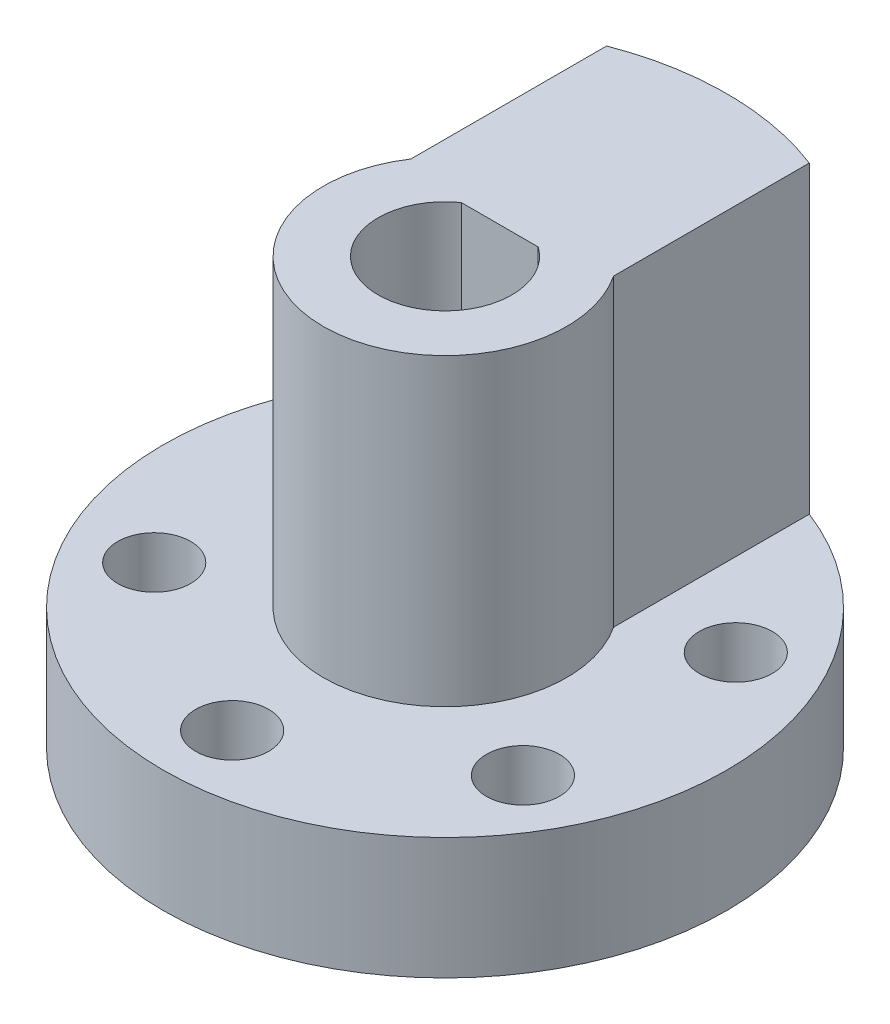
SolidWorks part; units mm, degrees
ref_plane "Plan de face" through (0, 0, 0) normal (0, 0, 1) x (1, 0, 0)
ref_plane "Plan de dessus" through (0, 0, 0) normal (0, 1, 0) x (1, 0, 0)
ref_plane "Plan de droite" through (0, 0, 0) normal (1, 0, 0) x (0, 0, -1)
sketch "Esquisse3" plane through (0, 0, 0) normal (0, 1, 0) x (1, 0, 0)
  circle A0 centre (0, 0) radius 13.9
  circle A2 centre (0, 0) radius 10.5 construction
  circle A3 centre (0, 10.5) radius 1.8
  circle A4 centre (9.0933, 5.25) radius 1.8
  circle A5 centre (9.0933, -5.25) radius 1.8
  circle A6 centre (0, -10.5) radius 1.8
  circle A7 centre (-9.0933, -5.25) radius 1.8
  circle A8 centre (-9.0933, 5.25) radius 1.8
  point P3 (0, 0)
  point P20 (0, 0)
  dimension "D1" = 27.8
  dimension "D2" = 6
  dimension "D3" = 21
  dimension "D4" = 3.6
extrude "Boss.-Extru.1" add sketch "Esquisse3" along normal blind 6
sketch "Esquisse5" plane through (0, 6, 0) normal (0, 1, 0) x (1, 0, 0)
  circle A0 centre (0, 0) radius 6
  dimension "D1" = 12
extrude "Boss.-Extru.2" add sketch "Esquisse5" along normal blind 15
sketch "Esquisse6" plane through (0, 21, 0) normal (0, 1, 0) x (1, 0, 0)
  line L0 (-1.8974, 2.7) -> (1.8974, 2.7)
  arc A0 (-1.8974, 2.7) -> (1.8974, 2.7) centre (0, 0) ccw
  point P1 (0, -3.3)
  dimension "D1" = 6
  dimension "D2" = 3.3
extrude "Enlèv. mat.-Extru.2" cut sketch "Esquisse6" against normal blind 11.8
ref_plane "Plan1" through (0, 0, 6) normal (0, 0, 1) x (1, 0, 0)
ref_plane "Plan2" through (0, 0, -6) normal (0, 0, -1) x (-1, 0, 0)
sketch "Esquisse7" plane through (0, 0, -6) normal (0, 0, -1) x (-1, 0, 0)
  line L0 (6, 21) -> (-6, 21) construction
  line L1 (-5, 21) -> (5, 21)
  line L2 (-5, 21) -> (-5, 6)
  line L3 (-5, 6) -> (5, 6)
  line L4 (5, 21) -> (5, 6)
  line L5 (-5, 21) -> (5, 6) construction
  line L6 (-5, 6) -> (5, 21) construction
  line L7 (6, 6) -> (-6, 6) construction
  point P3 (0, 21)
  point P9 (0, 0)
  dimension "D3" = 10
extrude "Boss.-Extru.3" add sketch "Esquisse7" along normal up to surface (9.9696 mm away) from offset 3 offset against normal yes
ref_plane "Plan3" through (0, 0, -13.9) normal (0, 0, -1) x (-1, 0, 0)
sketch "Esquisse11" plane through (0, 0, -13.9) normal (0, 0, -1) x (-1, 0, 0)
  circle A0 centre (0, 12.7074) radius 2.2
  point P2 (0, 12.6831)
  point P3 (0, 12.7074)
  point P5 (0, 0)
  dimension "D1" = 4.4
  dimension "D2" = 12.7074
extrude "Enlèv. mat.-Extru.3" cut sketch "Esquisse11" against normal blind 14
sketch "Esquisse12" plane through (0, 0, -13.9) normal (0, 0, -1) x (-1, 0, 0)
  line L3 (0, 16.3577) -> (-2.1075, 16.3577)
  line L4 (-2.1075, 16.3577) -> (-4.215, 12.7074)
  line L5 (-4.215, 12.7074) -> (-2.1075, 9.0571)
  line L6 (-2.1075, 9.0571) -> (2.1075, 9.0571)
  line L7 (5, 6) -> (5, 21) construction
  line L8 (5, 16.3577) -> (5, 9.0571)
  line L9 (5, 9.0571) -> (2.1075, 9.0571)
  line L10 (0, 16.3577) -> (5, 16.3577)
  line L11 (4.215, 12.7074) -> (3.1612, 14.5325) [skipped]
  line L12 (2.1075, 9.0571) -> (3.1613, 10.8822) [skipped]
  arc A0 (0, 16.3577) -> (0, 9.0571) centre (0, 12.7074) ccw construction
  point P3 (0, 0)
  point P4 (2.1075, 9.0571)
  point P8 (5, 9.0571)
  point P19 (0, 12.7074)
  point P20 (-2.2, 16.3577)
  point P21 (-4.215, 12.7074)
  point P22 (-2.1075, 9.0571)
  point P23 (5, 16.3577)
  point P24 (0, 12.7074)
  point P25 (0, 0)
  point P26 (5, 9.0571)
  point P27 (2.1075, 9.0571)
  dimension "D1" = 8.43
  dimension "D2" = 7.3006
extrude "Enlèv. mat.-Extru.4" cut sketch "Esquisse12" against normal blind 3.5 from offset 5 offset against normal yes
